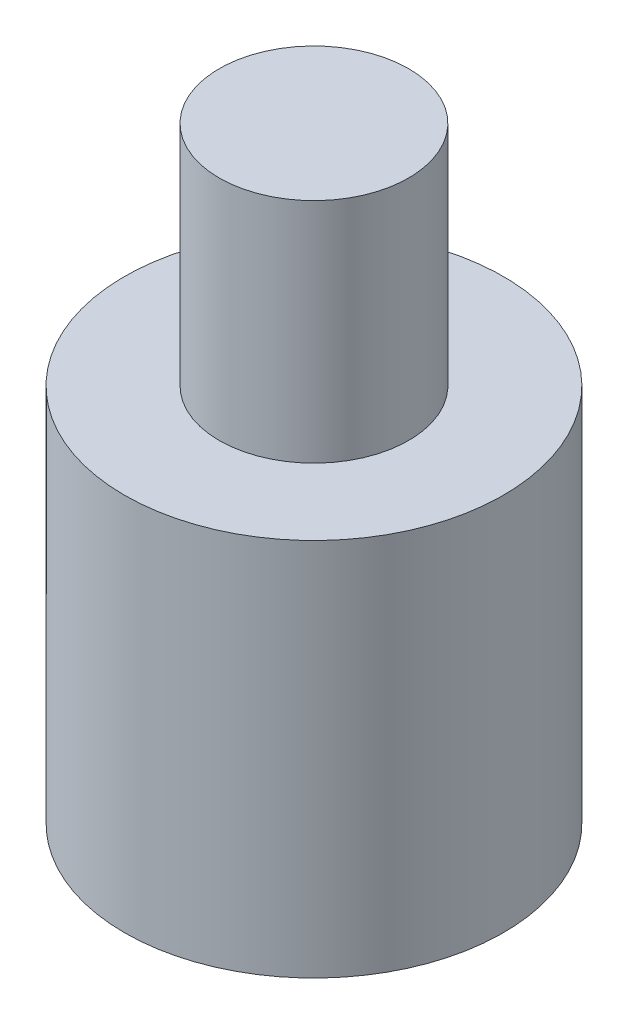
SolidWorks part; units mm, degrees
ref_plane "Front Plane" through (0, 0, 0) normal (0, 0, 1) x (1, 0, 0)
ref_plane "Top Plane" through (0, 0, 0) normal (0, 1, 0) x (1, 0, 0)
ref_plane "Right Plane" through (0, 0, 0) normal (1, 0, 0) x (0, 0, -1)
sketch "Sketch1" plane through (0, 0, 0) normal (0, 1, 0) x (1, 0, 0)
  circle A0 centre (0, 0) radius 2.5
  dimension "D1" = 5
extrude "Boss-Extrude1" add sketch "Sketch1" along normal blind 5
sketch "Sketch2" plane through (0, 5, 0) normal (0, 1, 0) x (1, 0, 0)
  circle A0 centre (0, 0) radius 1.25
  dimension "D1" = 2.5
extrude "Boss-Extrude2" add sketch "Sketch2" along normal blind 3
